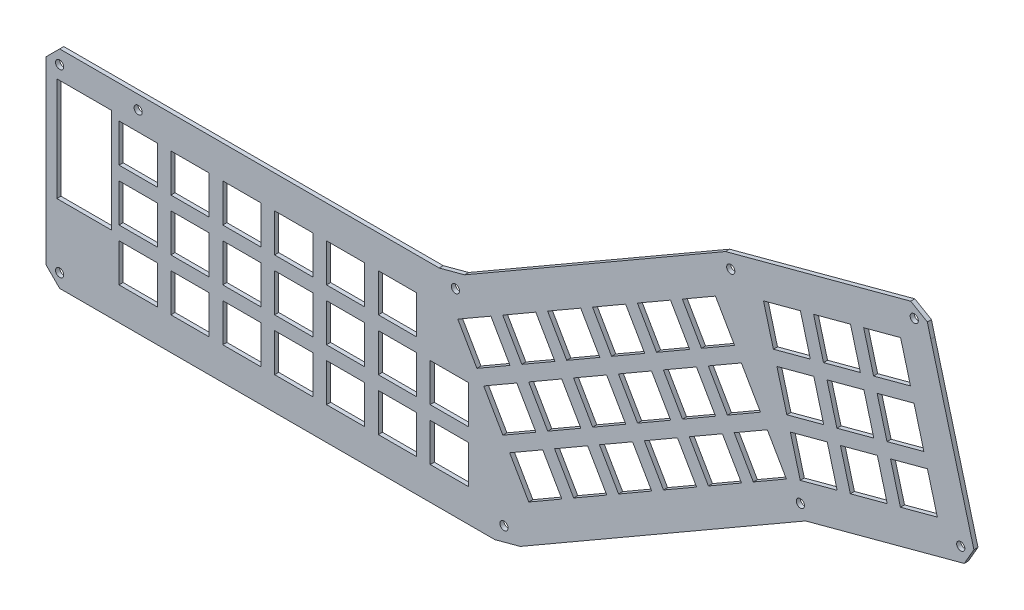
SolidWorks part; units mm, degrees
ref_plane "Plan de face" through (0, 0, 0) normal (0, 0, 1) x (1, 0, 0)
ref_plane "Plan de dessus" through (0, 0, 0) normal (0, 1, 0) x (1, 0, 0)
ref_plane "Plan de droite" through (0, 0, 0) normal (1, 0, 0) x (0, 0, -1)
sketch "Esquisse1" plane through (0, 0, 0) normal (0, 0, 1) x (1, 0, 0)
  line L0 (-73.9886, 18.0851) -> (-59.9886, 18.0851)
  line L1 (-73.9886, 37.0851) -> (-59.9886, 37.0851)
  line L2 (-73.9886, 37.0851) -> (-73.9886, 23.0851)
  line L3 (-73.9886, 23.0851) -> (-59.9886, 23.0851)
  line L4 (-59.9886, 37.0851) -> (-59.9886, 23.0851)
  line L5 (-73.9886, 18.0851) -> (-73.9886, 4.0851)
  line L6 (-73.9886, 4.0851) -> (-59.9886, 4.0851)
  line L7 (-59.9886, 18.0851) -> (-59.9886, 4.0851)
  line L8 (-73.9886, -0.9149) -> (-59.9886, -0.9149)
  line L9 (-73.9886, -0.9149) -> (-73.9886, -14.9149)
  line L10 (-73.9886, -14.9149) -> (-59.9886, -14.9149)
  line L11 (-59.9886, -0.9149) -> (-59.9886, -14.9149)
  line L12 (-73.9886, 37.0851) -> (-73.9886, 18.0851) construction
  line L13 (-54.9886, 18.0851) -> (-40.9886, 18.0851)
  line L14 (-54.9886, 37.0851) -> (-40.9886, 37.0851)
  line L15 (-54.9886, 37.0851) -> (-54.9886, 23.0851)
  line L16 (-54.9886, 23.0851) -> (-40.9886, 23.0851)
  line L17 (-40.9886, 37.0851) -> (-40.9886, 23.0851)
  line L18 (-54.9886, 18.0851) -> (-54.9886, 4.0851)
  line L19 (-54.9886, 4.0851) -> (-40.9886, 4.0851)
  line L20 (-40.9886, 18.0851) -> (-40.9886, 4.0851)
  line L21 (-54.9886, -0.9149) -> (-40.9886, -0.9149)
  line L22 (-54.9886, -0.9149) -> (-54.9886, -14.9149)
  line L23 (-54.9886, -14.9149) -> (-40.9886, -14.9149)
  line L24 (-40.9886, -0.9149) -> (-40.9886, -14.9149)
  line L25 (-54.9886, 37.0851) -> (-54.9886, 18.0851) construction
  line L26 (-35.9886, 18.0851) -> (-21.9886, 18.0851)
  line L27 (-35.9886, 37.0851) -> (-21.9886, 37.0851)
  line L28 (-35.9886, 37.0851) -> (-35.9886, 23.0851)
  line L29 (-35.9886, 23.0851) -> (-21.9886, 23.0851)
  line L30 (-21.9886, 37.0851) -> (-21.9886, 23.0851)
  line L31 (-35.9886, 18.0851) -> (-35.9886, 4.0851)
  line L32 (-35.9886, 4.0851) -> (-21.9886, 4.0851)
  line L33 (-21.9886, 18.0851) -> (-21.9886, 4.0851)
  line L34 (-35.9886, -0.9149) -> (-21.9886, -0.9149)
  line L35 (-35.9886, -0.9149) -> (-35.9886, -14.9149)
  line L36 (-35.9886, -14.9149) -> (-21.9886, -14.9149)
  line L37 (-21.9886, -0.9149) -> (-21.9886, -14.9149)
  line L38 (-35.9886, 37.0851) -> (-35.9886, 18.0851) construction
  line L39 (-16.9886, 18.0851) -> (-2.9886, 18.0851)
  line L40 (-16.9886, 37.0851) -> (-2.9886, 37.0851)
  line L41 (-16.9886, 37.0851) -> (-16.9886, 23.0851)
  line L42 (-16.9886, 23.0851) -> (-2.9886, 23.0851)
  line L43 (-2.9886, 37.0851) -> (-2.9886, 23.0851)
  line L44 (-16.9886, 18.0851) -> (-16.9886, 4.0851)
  line L45 (-16.9886, 4.0851) -> (-2.9886, 4.0851)
  line L46 (-2.9886, 18.0851) -> (-2.9886, 4.0851)
  line L47 (-16.9886, -0.9149) -> (-2.9886, -0.9149)
  line L48 (-16.9886, -0.9149) -> (-16.9886, -14.9149)
  line L49 (-16.9886, -14.9149) -> (-2.9886, -14.9149)
  line L50 (-2.9886, -0.9149) -> (-2.9886, -14.9149)
  line L51 (-16.9886, 37.0851) -> (-16.9886, 18.0851) construction
  line L52 (2.0114, 18.0851) -> (16.0114, 18.0851)
  line L53 (2.0114, 37.0851) -> (16.0114, 37.0851)
  line L54 (2.0114, 37.0851) -> (2.0114, 23.0851)
  line L55 (2.0114, 23.0851) -> (16.0114, 23.0851)
  line L56 (16.0114, 37.0851) -> (16.0114, 23.0851)
  line L57 (2.0114, 18.0851) -> (2.0114, 4.0851)
  line L58 (2.0114, 4.0851) -> (16.0114, 4.0851)
  line L59 (16.0114, 18.0851) -> (16.0114, 4.0851)
  line L60 (2.0114, -0.9149) -> (16.0114, -0.9149)
  line L61 (2.0114, -0.9149) -> (2.0114, -14.9149)
  line L62 (2.0114, -14.9149) -> (16.0114, -14.9149)
  line L63 (16.0114, -0.9149) -> (16.0114, -14.9149)
  line L64 (2.0114, 37.0851) -> (2.0114, 18.0851) construction
  line L65 (21.0114, 18.0851) -> (35.0114, 18.0851)
  line L66 (21.0114, 37.0851) -> (35.0114, 37.0851)
  line L67 (21.0114, 37.0851) -> (21.0114, 23.0851)
  line L68 (21.0114, 23.0851) -> (35.0114, 23.0851)
  line L69 (35.0114, 37.0851) -> (35.0114, 23.0851)
  line L70 (21.0114, 18.0851) -> (21.0114, 4.0851)
  line L71 (21.0114, 4.0851) -> (35.0114, 4.0851)
  line L72 (35.0114, 18.0851) -> (35.0114, 4.0851)
  line L73 (21.0114, -0.9149) -> (35.0114, -0.9149)
  line L74 (21.0114, -0.9149) -> (21.0114, -14.9149)
  line L75 (21.0114, -14.9149) -> (35.0114, -14.9149)
  line L76 (35.0114, -0.9149) -> (35.0114, -14.9149)
  line L77 (21.0114, 37.0851) -> (21.0114, 18.0851) construction
  line L78 (40.0114, 18.0851) -> (54.0114, 18.0851)
  line L79 (40.0114, 37.0851) -> (54.0114, 37.0851) construction
  line L80 (40.0114, 37.0851) -> (40.0114, 23.0851) construction
  line L81 (40.0114, 23.0851) -> (54.0114, 23.0851) construction
  line L82 (54.0114, 37.0851) -> (54.0114, 23.0851) construction
  line L83 (40.0114, 18.0851) -> (40.0114, 4.0851)
  line L84 (40.0114, 4.0851) -> (54.0114, 4.0851)
  line L85 (54.0114, 18.0851) -> (54.0114, 4.0851)
  line L86 (40.0114, -0.9149) -> (54.0114, -0.9149)
  line L87 (40.0114, -0.9149) -> (40.0114, -14.9149)
  line L88 (40.0114, -14.9149) -> (54.0114, -14.9149)
  line L89 (54.0114, -0.9149) -> (54.0114, -14.9149)
  line L90 (40.0114, 37.0851) -> (40.0114, 18.0851) construction
  line L91 (-73.9886, 18.0851) -> (-54.9886, 18.0851) construction
  line L92 (56.0114, 20.0851) -> (56.7532, 18.8002) construction
  line L93 (38.0114, 39.0851) -> (56.0114, 39.0851) construction
  line L94 (56.0114, 39.0851) -> (56.0114, 21.0851) construction
  line L95 (38.0114, 21.0851) -> (56.0114, 21.0851) construction
  line L96 (38.0114, 39.0851) -> (38.0114, 21.0851) construction
  line L97 (19.0114, 39.0851) -> (37.0114, 39.0851) construction
  line L98 (37.0114, 39.0851) -> (37.0114, 21.0851) construction
  line L99 (19.0114, 21.0851) -> (37.0114, 21.0851) construction
  line L100 (19.0114, 39.0851) -> (19.0114, 21.0851) construction
  line L101 (79.4363, 55.512) -> (88.4363, 39.9235) construction
  line L102 (88.4363, 39.9235) -> (72.8478, 30.9235) construction
  line L103 (63.8478, 46.512) -> (72.8478, 30.9235) construction
  line L104 (79.4363, 55.512) -> (63.8478, 46.512) construction
  line L105 (62.9818, 46.012) -> (71.9818, 30.4235) construction
  line L106 (71.9818, 30.4235) -> (56.3933, 21.4235) construction
  line L107 (47.3933, 37.012) -> (56.3933, 21.4235) construction
  line L108 (62.9818, 46.012) -> (47.3933, 37.012) construction
  line L109 (164.2542, 60.603) -> (148.6657, 51.603) construction
  line L110 (62.2497, 43.2799) -> (71.7497, 26.8254) construction
  line L111 (78.7042, 52.7799) -> (88.2042, 36.3254) construction
  line L112 (95.1587, 62.2799) -> (104.6587, 45.8254) construction
  line L113 (111.6132, 71.7799) -> (121.1132, 55.3254) construction
  line L114 (128.0677, 81.2799) -> (137.5677, 64.8254) construction
  line L115 (144.5221, 90.7799) -> (154.0221, 74.3254) construction
  line L116 (148.6657, 51.603) -> (157.6657, 36.0146) construction
  line L117 (69.1254, 3.371) -> (76.1254, -8.7534)
  line L118 (88.2497, -1.7534) -> (76.1254, -8.7534)
  line L119 (81.2497, 10.371) -> (88.2497, -1.7534)
  line L120 (81.2497, 10.371) -> (69.1254, 3.371)
  line L121 (59.6254, 19.8254) -> (66.6254, 7.7011)
  line L122 (78.7497, 14.7011) -> (66.6254, 7.7011)
  line L123 (71.7497, 26.8254) -> (78.7497, 14.7011)
  line L124 (50.1254, 36.2799) -> (57.1254, 24.1556)
  line L125 (69.2497, 31.1556) -> (57.1254, 24.1556)
  line L126 (62.2497, 43.2799) -> (69.2497, 31.1556)
  line L127 (62.2497, 43.2799) -> (50.1254, 36.2799)
  line L128 (71.7497, 26.8254) -> (59.6254, 19.8254)
  line L129 (85.5799, 12.871) -> (92.5799, 0.7466)
  line L130 (104.7042, 7.7466) -> (92.5799, 0.7466)
  line L131 (97.7042, 19.871) -> (104.7042, 7.7466)
  line L132 (97.7042, 19.871) -> (85.5799, 12.871)
  line L133 (76.0799, 29.3254) -> (83.0799, 17.2011)
  line L134 (95.2042, 24.2011) -> (83.0799, 17.2011)
  line L135 (88.2042, 36.3254) -> (95.2042, 24.2011)
  line L136 (66.5799, 45.7799) -> (73.5799, 33.6556)
  line L137 (85.7042, 40.6556) -> (73.5799, 33.6556)
  line L138 (78.7042, 52.7799) -> (85.7042, 40.6556)
  line L139 (78.7042, 52.7799) -> (66.5799, 45.7799)
  line L140 (88.2042, 36.3254) -> (76.0799, 29.3254)
  line L141 (102.0343, 22.371) -> (109.0343, 10.2466)
  line L142 (121.1587, 17.2466) -> (109.0343, 10.2466)
  line L143 (114.1587, 29.371) -> (121.1587, 17.2466)
  line L144 (114.1587, 29.371) -> (102.0343, 22.371)
  line L145 (92.5343, 38.8254) -> (99.5343, 26.7011)
  line L146 (111.6587, 33.7011) -> (99.5343, 26.7011)
  line L147 (104.6587, 45.8254) -> (111.6587, 33.7011)
  line L148 (83.0343, 55.2799) -> (90.0343, 43.1556)
  line L149 (102.1587, 50.1556) -> (90.0343, 43.1556)
  line L150 (95.1587, 62.2799) -> (102.1587, 50.1556)
  line L151 (95.1587, 62.2799) -> (83.0343, 55.2799)
  line L152 (104.6587, 45.8254) -> (92.5343, 38.8254)
  line L153 (118.4888, 31.871) -> (125.4888, 19.7466)
  line L154 (137.6132, 26.7466) -> (125.4888, 19.7466)
  line L155 (130.6132, 38.871) -> (137.6132, 26.7466)
  line L156 (130.6132, 38.871) -> (118.4888, 31.871)
  line L157 (108.9888, 48.3254) -> (115.9888, 36.2011)
  line L158 (128.1132, 43.2011) -> (115.9888, 36.2011)
  line L159 (121.1132, 55.3254) -> (128.1132, 43.2011)
  line L160 (99.4888, 64.7799) -> (106.4888, 52.6556)
  line L161 (118.6132, 59.6556) -> (106.4888, 52.6556)
  line L162 (111.6132, 71.7799) -> (118.6132, 59.6556)
  line L163 (111.6132, 71.7799) -> (99.4888, 64.7799)
  line L164 (121.1132, 55.3254) -> (108.9888, 48.3254)
  line L165 (134.9433, 41.371) -> (141.9433, 29.2466)
  line L166 (154.0677, 36.2466) -> (141.9433, 29.2466)
  line L167 (147.0677, 48.371) -> (154.0677, 36.2466)
  line L168 (147.0677, 48.371) -> (134.9433, 41.371)
  line L169 (125.4433, 57.8254) -> (132.4433, 45.7011)
  line L170 (144.5677, 52.7011) -> (132.4433, 45.7011)
  line L171 (137.5677, 64.8254) -> (144.5677, 52.7011)
  line L172 (115.9433, 74.2799) -> (122.9433, 62.1556)
  line L173 (135.0677, 69.1556) -> (122.9433, 62.1556)
  line L174 (128.0677, 81.2799) -> (135.0677, 69.1556)
  line L175 (128.0677, 81.2799) -> (115.9433, 74.2799)
  line L176 (137.5677, 64.8254) -> (125.4433, 57.8254)
  line L177 (151.3978, 50.871) -> (158.3978, 38.7466)
  line L178 (170.5221, 45.7466) -> (158.3978, 38.7466)
  line L179 (163.5221, 57.871) -> (170.5221, 45.7466)
  line L180 (163.5221, 57.871) -> (151.3978, 50.871)
  line L181 (141.8978, 67.3254) -> (148.8978, 55.2011)
  line L182 (161.0221, 62.2011) -> (148.8978, 55.2011)
  line L183 (154.0221, 74.3254) -> (161.0221, 62.2011)
  line L184 (132.3978, 83.7799) -> (139.3978, 71.6556)
  line L185 (151.5221, 78.6556) -> (139.3978, 71.6556)
  line L186 (144.5221, 90.7799) -> (151.5221, 78.6556)
  line L187 (144.5221, 90.7799) -> (132.3978, 83.7799)
  line L188 (154.0221, 74.3254) -> (141.8978, 67.3254)
  line L189 (173.2542, 45.0146) -> (157.6657, 36.0146) construction
  line L190 (164.2542, 60.603) -> (173.2542, 45.0146) construction
  line L191 (178.3169, 34.0986) -> (169.0534, 56.4627) construction
  line L192 (169.5193, 62.7839) -> (174.1781, 45.3972) construction
  line L193 (174.1781, 45.3972) -> (191.5647, 50.056) construction
  line L194 (186.906, 67.4426) -> (191.5647, 50.056) construction
  line L195 (162.1337, 98.0749) -> (167.0513, 79.7223) construction
  line L196 (169.5193, 62.7839) -> (186.906, 67.4426) construction
  line L197 (167.0513, 79.7223) -> (180.5742, 83.3457)
  line L198 (162.1337, 98.0749) -> (175.6567, 101.6983)
  line L199 (162.1337, 98.0749) -> (165.7572, 84.5519)
  line L200 (165.7572, 84.5519) -> (179.2801, 88.1754)
  line L201 (175.6567, 101.6983) -> (179.2801, 88.1754)
  line L202 (167.0513, 79.7223) -> (170.6747, 66.1993)
  line L203 (170.6747, 66.1993) -> (184.1977, 69.8228)
  line L204 (180.5742, 83.3457) -> (184.1977, 69.8228)
  line L205 (171.9688, 61.3697) -> (185.4918, 64.9932)
  line L206 (171.9688, 61.3697) -> (175.5923, 47.8467)
  line L207 (175.5923, 47.8467) -> (189.1152, 51.4702)
  line L208 (185.4918, 64.9932) -> (189.1152, 51.4702)
  line L209 (185.4038, 84.6398) -> (198.9268, 88.2633)
  line L210 (180.4863, 102.9924) -> (194.0092, 106.6159)
  line L211 (180.4863, 102.9924) -> (184.1097, 89.4695)
  line L212 (184.1097, 89.4695) -> (197.6327, 93.0929)
  line L213 (194.0092, 106.6159) -> (197.6327, 93.0929)
  line L214 (185.4038, 84.6398) -> (189.0273, 71.1169)
  line L215 (189.0273, 71.1169) -> (202.5503, 74.7403)
  line L216 (198.9268, 88.2633) -> (202.5503, 74.7403)
  line L217 (190.3214, 66.2873) -> (203.8444, 69.9107)
  line L218 (190.3214, 66.2873) -> (193.9449, 52.7643)
  line L219 (193.9449, 52.7643) -> (207.4678, 56.3878)
  line L220 (203.8444, 69.9107) -> (207.4678, 56.3878)
  line L221 (187.8719, 67.7015) -> (192.5307, 50.3148) construction
  line L222 (192.5307, 50.3148) -> (209.9173, 54.9735) construction
  line L223 (205.2586, 72.3602) -> (209.9173, 54.9735) construction
  line L224 (180.4863, 102.9924) -> (185.4038, 84.6398) construction
  line L225 (187.8719, 67.7015) -> (205.2586, 72.3602) construction
  line L226 (203.7564, 89.5574) -> (217.2794, 93.1809)
  line L227 (198.8389, 107.91) -> (212.3618, 111.5335)
  line L228 (198.8389, 107.91) -> (202.4623, 94.387)
  line L229 (202.4623, 94.387) -> (215.9853, 98.0105)
  line L230 (212.3618, 111.5335) -> (215.9853, 98.0105)
  line L231 (203.7564, 89.5574) -> (207.3799, 76.0344)
  line L232 (207.3799, 76.0344) -> (220.9029, 79.6579)
  line L233 (217.2794, 93.1809) -> (220.9029, 79.6579)
  line L234 (208.674, 71.2048) -> (222.197, 74.8283)
  line L235 (208.674, 71.2048) -> (212.2975, 57.6819)
  line L236 (212.2975, 57.6819) -> (225.8204, 61.3053)
  line L237 (222.197, 74.8283) -> (225.8204, 61.3053)
  line L238 (206.2245, 72.619) -> (210.8833, 55.2324) construction
  line L239 (210.8833, 55.2324) -> (228.2699, 59.8911) construction
  line L240 (223.6112, 77.2778) -> (228.2699, 59.8911) construction
  line L241 (198.8389, 107.91) -> (203.7564, 89.5574) construction
  line L242 (206.2245, 72.619) -> (223.6112, 77.2778) construction
  line L243 (167.0513, 79.7223) -> (185.4038, 84.6398) construction
  line L244 (38.0114, 20.0851) -> (56.0114, 20.0851) construction
  line L245 (56.0114, 20.0851) -> (56.0114, 2.0851) construction
  line L246 (38.0114, 2.0851) -> (56.0114, 2.0851) construction
  line L247 (38.0114, 20.0851) -> (38.0114, 2.0851) construction
  line L248 (72.4818, 29.5575) -> (56.8933, 20.5575) construction
  line L249 (56.8933, 20.5575) -> (65.8933, 4.969) construction
  line L250 (81.4818, 13.969) -> (65.8933, 4.969) construction
  line L251 (72.4818, 29.5575) -> (81.4818, 13.969) construction
  line L252 (56.8933, 20.5575) -> (57.6111, 19.3142) construction
  line L253 (164.6018, 81.1365) -> (169.2605, 63.7498) construction
  line L254 (169.2605, 63.7498) -> (186.6472, 68.4086) construction
  line L255 (181.9884, 85.7952) -> (186.6472, 68.4086) construction
  line L256 (164.6018, 81.1365) -> (181.9884, 85.7952) construction
  line L257 (154.7542, 77.0575) -> (163.7542, 61.469) construction
  line L258 (163.7542, 61.469) -> (148.1657, 52.469) construction
  line L259 (139.1657, 68.0575) -> (148.1657, 52.469) construction
  line L260 (154.7542, 77.0575) -> (139.1657, 68.0575) construction
  line L261 (196.3894, 109.3242) -> (213.776, 113.983) construction
  line L262 (-94.7538, 35.7952) -> (-76.7538, 35.7952) construction
  line L263 (-94.7538, 35.7952) -> (-94.7538, 2.7952) construction
  line L264 (-94.7538, 2.7952) -> (-76.7538, 2.7952) construction
  line L265 (-76.7538, 35.7952) -> (-76.7538, 2.7952) construction
  line L266 (213.776, 113.983) -> (218.4348, 96.5963) construction
  line L267 (201.0481, 91.9375) -> (218.4348, 96.5963) construction
  line L268 (196.3894, 109.3242) -> (201.0481, 91.9375) construction
  line L269 (-75.9886, -16.9149) -> (-57.9886, -16.9149) construction
  line L270 (-57.9886, 1.0851) -> (-57.9886, -16.9149) construction
  line L271 (-75.9886, 1.0851) -> (-57.9886, 1.0851) construction
  line L272 (-75.9886, 1.0851) -> (-75.9886, -16.9149) construction
  line L273 (38.0114, -16.9149) -> (56.0114, -16.9149) construction
  line L274 (56.0114, 1.0851) -> (56.0114, -16.9149) construction
  line L275 (38.0114, 1.0851) -> (56.0114, 1.0851) construction
  line L276 (38.0114, 1.0851) -> (38.0114, -16.9149) construction
  line L277 (-75.9886, 39.0851) -> (-57.9886, 39.0851) construction
  line L278 (-57.9886, 39.0851) -> (-57.9886, 21.0851) construction
  line L279 (-75.9886, 21.0851) -> (-57.9886, 21.0851) construction
  line L280 (-75.9886, 39.0851) -> (-75.9886, 21.0851) construction
  line L281 (145.2542, 93.512) -> (129.6657, 84.512) construction
  line L282 (129.6657, 84.512) -> (138.6657, 68.9235) construction
  line L283 (154.2542, 77.9235) -> (138.6657, 68.9235) construction
  line L284 (145.2542, 93.512) -> (154.2542, 77.9235) construction
  line L285 (223.4353, 116.5711) -> (228.0941, 99.1845)
  line L286 (148.2159, 106.7689) -> (211.1879, 123.6422)
  line L287 (177.5508, 35.9482) -> (235.6877, 51.5259)
  line L288 (177.5508, 35.9482) -> (72.9989, -24.4149)
  line L289 (-95.7538, -26.9149) -> (63.6687, -26.9149)
  line L290 (-100.7538, 35.7952) -> (-100.7538, -21.9149)
  line L291 (-75.9886, 49.0851) -> (43.3046, 49.0851)
  line L292 (148.2159, 106.7689) -> (52.6347, 51.5851)
  line L293 (-75.9886, 49.0851) -> (-57.9886, 49.0851) construction
  line L294 (140.2542, 102.1722) -> (124.6657, 93.1722) construction
  line L295 (193.8012, 118.9835) -> (211.1879, 123.6422) construction
  line L296 (213.4714, 45.5731) -> (230.8581, 50.2318) construction
  line L297 (38.0114, -26.9149) -> (38.0114, -85.4624) construction
  line L298 (178.2542, 36.3543) -> (162.6657, 27.3543) construction
  line L299 (38.0114, -26.9149) -> (56.0114, -26.9149) construction
  line L300 (-100.7538, 2.7952) -> (-100.7538, -38.0419) construction
  line L301 (-100.7538, 35.7952) -> (-100.7538, 2.7952) construction
  line L302 (-75.9886, 49.0851) -> (-95.7538, 49.0851)
  line L303 (-100.7538, 44.0851) -> (-100.7538, 35.7952)
  line L304 (211.1879, 123.6422) -> (216.0732, 124.9512)
  line L305 (222.1691, 121.4083) -> (223.4353, 116.5711)
  line L306 (228.0941, 99.1845) -> (239.2233, 57.6497)
  line L307 (216.0732, 124.9512) -> (222.1691, 121.4083)
  line L308 (235.6877, 51.5259) -> (239.2233, 57.6497)
  line L309 (63.6687, -26.9149) -> (72.9989, -24.4149)
  line L310 (52.6347, 51.5851) -> (43.3046, 49.0851)
  line L311 (-95.7538, 49.0851) -> (-100.7538, 44.0851)
  line L312 (-100.7538, -21.9149) -> (-95.7538, -26.9149)
  line L313 (-95.7538, 49.0851) -> (-95.7538, 44.0851) construction
  line L314 (-95.7538, 44.0851) -> (-100.7538, 44.0851) construction
  line L315 (-95.7538, -26.9149) -> (-95.7538, -21.9149) construction
  line L316 (68.3338, -25.6649) -> (67.0397, -20.8353) construction
  line L317 (47.9697, 50.3351) -> (49.2637, 45.5055) construction
  line L318 (177.5508, 35.9482) -> (175.6374, 40.5676) construction
  line L319 (148.2159, 106.7689) -> (150.1293, 102.1495) construction
  line L320 (239.2233, 57.6497) -> (234.3936, 56.3556) construction
  line L321 (216.0732, 124.9512) -> (217.3634, 120.1206) construction
  line L322 (-66.9886, 37.0851) -> (-66.9886, 49.0851) construction
  line L323 (-76.7538, 35.7952) -> (-96.7538, 35.7952) construction
  line L324 (-95.7538, 44.0851) -> (-65.1374, 44.0851) construction
  line L325 (-76.7538, 39.0851) -> (-96.7538, 39.0851)
  line L326 (-76.7538, 39.0851) -> (-76.7538, 1.0851)
  line L327 (-76.7538, 1.0851) -> (-96.7538, 1.0851)
  line L328 (-96.7538, 39.0851) -> (-96.7538, 1.0851)
  circle A0 centre (-95.7538, 44.0851) radius 1.5
  circle A1 centre (-95.7538, -21.9149) radius 1.5
  circle A2 centre (67.0397, -20.8353) radius 1.5
  circle A3 centre (49.2637, 45.5055) radius 1.5
  circle A4 centre (175.6374, 40.5676) radius 1.5
  circle A5 centre (150.1293, 102.1495) radius 1.5
  circle A6 centre (234.3936, 56.3556) radius 1.5
  circle A7 centre (217.3634, 120.1206) radius 1.5
  circle A8 centre (-66.9886, 44.0851) radius 1.5
  point P304 (48.3046, 49.0851)
  point P305 (240.5174, 52.82)
  point P308 (68.6687, -26.9149)
  point P309 (-100.7538, -26.9149)
  point P311 (-100.7538, 49.0851)
  point P312 (220.9029, 126.2453)
  point P353 (0, 0)
  dimension "D32" = 3
  dimension "D33" = 5
  dimension "D40" = 5
  dimension "D41" = 5
  dimension "D42" = 5
  dimension "D43" = 5
  dimension "D44" = 20
  dimension "D1" = 14
  dimension "D2" = 14
  dimension "D4" = 19
  dimension "D6" = 19
  dimension "D7" = 30
  dimension "D10" = 1
  dimension "D11" = 2
  dimension "D13" = 0.5
  dimension "D15" = 2
  dimension "D12" = 7.5
  dimension "D14" = 19
  dimension "D18" = 2
  dimension "D20" = 18
  dimension "D21" = 33
  dimension "D22" = 2
  dimension "D8" = 2
  dimension "D9" = 2
  dimension "D16" = 2
  dimension "D19" = 2
  dimension "D23" = 2
  dimension "D24" = 10
  dimension "D25" = 10
  dimension "D26" = 10
  dimension "D27" = 10
  dimension "D28" = 10
  dimension "D29" = 6
  dimension "D30" = 10
  dimension "D31" = 10
  dimension "D3" = 3
  dimension "D5" = 7
  dimension "D17" = 3
extrude "Boss.-Extru.1" add sketch "Esquisse1" along normal blind 1.5
